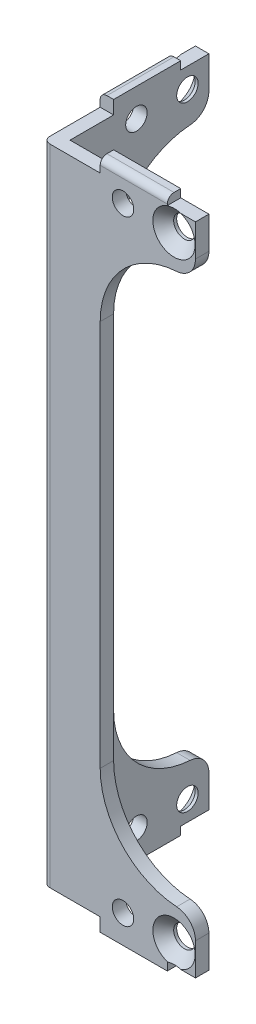
SolidWorks part; units mm, degrees
material "PETG"
ref_plane "Front Plane" through (0, 0, 0) normal (0, 0, 1) x (1, 0, 0)
ref_plane "Top Plane" through (0, 0, 0) normal (0, 1, 0) x (1, 0, 0)
ref_plane "Right Plane" through (0, 0, 0) normal (1, 0, 0) x (0, 0, -1)
sketch "Sketch5" plane through (0, 0, 0) normal (0, 1, 0) x (1, 0, 0)
  line L0 (0, 8.5) -> (0, 0)
  line L1 (0, 0) -> (8.5, 0)
  line L2 (8.5, 0) -> (8.5, 2)
  line L3 (8.5, 2) -> (2, 2)
  line L4 (2, 2) -> (2, 8.5)
  line L5 (2, 8.5) -> (0, 8.5)
  dimension "D1" = 8.5
  dimension "D2" = 2
extrude "Boss-Extrude3" add sketch "Sketch5" along normal mid plane 96
sketch "Sketch9" plane through (0, 0, 0) normal (0, 0, 1) x (1, 0, 0)
  line L1 (8.5, 50) -> (18.5, 50)
  line L2 (8.5, 50) -> (8.5, 41)
  line L3 (8.5, 41) -> (19.7, 41)
  line L4 (22.7, 48.8) -> (22.7, 44)
  line L5 (0, 48) -> (8.5, 48) construction
  line L6 (8.5, 48) -> (8.5, -48) construction
  line L7 (18.5, 50) -> (18.5, 48.8)
  line L8 (18.5, 48.8) -> (22.7, 48.8)
  arc A0 (19.7, 41) -> (22.7, 44) centre (19.7, 44) ccw
  circle A1 centre (11.9, 45.8) radius 1.6
  circle A2 centre (19.5, 45.8) radius 1.6
  point P11 (22.7, 41)
  dimension "D4" = 3
  dimension "D7" = 7.6
  dimension "D8" = 3.2
  dimension "D9" = 4.2
  dimension "D10" = 3.4
  dimension "D11" = 4.2
  dimension "D2" = 2
  dimension "D3" = 10
  dimension "D5" = 9
  dimension "D6" = 1.2
extrude "Boss-Extrude5" add sketch "Sketch9" against normal up to surface (2 mm away) up to face at (5.25, 0, -2)
sketch "Sketch6" plane through (0, 0, 0) normal (-1, 0, 0) x (0, 0, 1)
  line L0 (-8.5, 48) -> (-8.5, -48) construction
  line L1 (-8.5, 41) -> (-19.7, 41)
  line L2 (-8.5, 41) -> (-8.5, 50)
  line L3 (-8.5, 50) -> (-18.5, 50)
  line L4 (-22.7, 44) -> (-22.7, 48.8)
  line L5 (-8.5, 48) -> (0, 48) construction
  line L6 (-22.7, 48.8) -> (-18.5, 48.8)
  line L7 (-18.5, 48.8) -> (-18.5, 50)
  arc A0 (-19.7, 41) -> (-22.7, 44) centre (-19.7, 44) cw
  circle A1 centre (-11.9, 45.8) radius 1.6
  circle A2 centre (-19.5, 45.8) radius 1.6
  point P10 (-22.7, 41)
  dimension "D4" = 3
  dimension "D7" = 3.2
  dimension "D8" = 3.4
  dimension "D9" = 7.6
  dimension "D10" = 4.2
  dimension "D1" = 2
  dimension "D2" = 4.2
  dimension "D3" = 10
  dimension "D5" = 1.2
  dimension "D6" = 9
extrude "Boss-Extrude6" add sketch "Sketch6" against normal up to surface (2 mm away) up to face at (2, 0, -5.25)
mirror "Mirror1" about plane through (0, 0, 0) normal (0, 1, 0) of "Boss-Extrude6", "Boss-Extrude5"
fillet "Fillet4" radius 1 3 edges at (0, 0, 0) (13.5, 50, 0) (0, 50, -13.5)
fillet "Fillet5" radius 12.2 4 edges at (8.5, -41, -1) (8.5, 41, -1) (1, 41, -8.5) (1, -41, -8.5)
hole_wizard "CSK for M3 Countersunk Flat Head Screw1" positions "Sketch10" profile "Sketch11" countersink size "M3" standard "DIN" end condition through all
sketch "Sketch10" plane through (0, 0, 0) normal (-1, 0, 0) x (0, 0, 1)
  point P0 (-19.5, 45.8)
sketch "Sketch11" plane through (0, 45.8, -19.5) normal (0, 1, 0) x (0, 0, 1)
  line L0 (0, 0) -> (0, 22.7)
  line L1 (0, 22.7) -> (1.6, 22.7)
  line L2 (1.6, 22.7) -> (1.6, 1.55)
  line L3 (1.6, 1.55) -> (3.15, 0)
  line L5 (3.15, 0) -> (0, 0)
  line L6 (-1.6, 1.55) -> (-3.15, 0) construction
  line L11 (0, -6.35) -> (0, 107.95) construction
  dimension "Thru Hole Dia." = 3.2
  dimension "Thru Hole Depth" = 22.7
  dimension "Near C'Sink Dia." = 6.3
  dimension "Near C'Sink Angle" = 90
hole_wizard "CSK for M3 Countersunk Flat Head Screw2" positions "Sketch13" profile "Sketch14" countersink size "M3" standard "DIN" end condition through all
sketch "Sketch13" plane through (0, 0, 0) normal (0, 0, 1) x (1, 0, 0)
  point P0 (19.5, 45.8)
sketch "Sketch14" plane through (19.5, 45.8, 0) normal (1, 0, 0) x (0, -1, 0)
  line L0 (0, 0) -> (0, 22.7)
  line L1 (0, 22.7) -> (1.6, 22.7)
  line L2 (1.6, 22.7) -> (1.6, 1.55)
  line L3 (1.6, 1.55) -> (3.15, 0)
  line L5 (3.15, 0) -> (0, 0)
  line L6 (-1.6, 1.55) -> (-3.15, 0) construction
  line L11 (0, -6.35) -> (0, 107.95) construction
  dimension "Thru Hole Dia." = 3.2
  dimension "Thru Hole Depth" = 22.7
  dimension "Near C'Sink Dia." = 6.3
  dimension "Near C'Sink Angle" = 90
mirror "Mirror2" about plane through (0, 0, 0) normal (0, 1, 0) of "CSK for M3 Countersunk Flat Head Screw2", "CSK for M3 Countersunk Flat Head Screw1"
